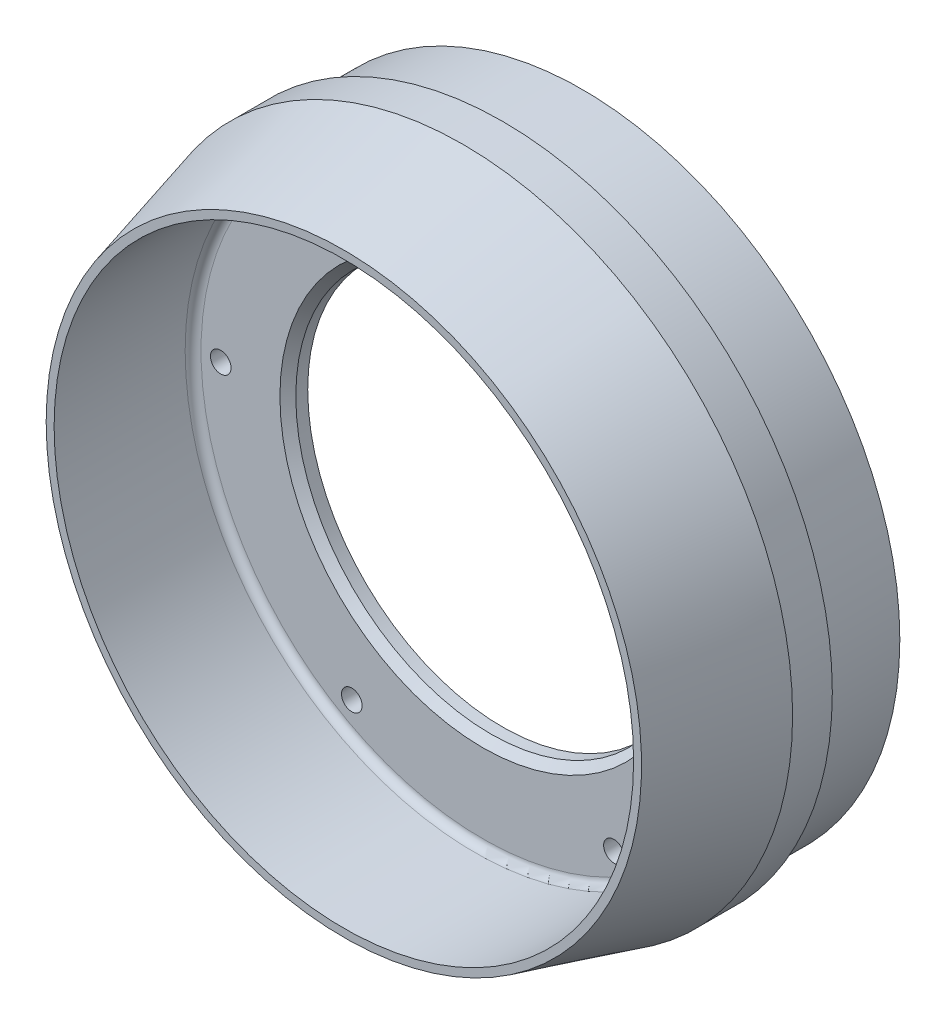
SolidWorks part; units mm, degrees
material "6061 Alloy"
ref_plane "Front Plane" through (0, 0, 0) normal (0, 0, 1) x (1, 0, 0)
ref_plane "Top Plane" through (0, 0, 0) normal (0, 1, 0) x (1, 0, 0)
ref_plane "Right Plane" through (0, 0, 0) normal (1, 0, 0) x (0, 0, -1)
sketch "Sketch2" plane through (0, 0, 0) normal (1, 0, 0) x (0, 0, -1)
  line L0 (-5, 83) -> (-35, 74.9615)
  line L1 (-35, 74.9615) -> (-35, 72.9615)
  line L2 (-35, 72.9615) -> (0, 72.9615)
  line L3 (0, 72.9615) -> (0, 49.1)
  line L5 (-5, 83) -> (5, 83)
  line L6 (0, 0) -> (0, 120.0745) construction
  line L8 (5, 77.5) -> (25, 77.5)
  line L9 (25, 77.5) -> (25, 80)
  line L10 (5, 80) -> (5, 83)
  line L11 (25, 80) -> (5, 80)
  line L12 (0, 49.1) -> (5, 49.1)
  line L14 (5, 49.1) -> (5, 77.5)
  point P1 (0, 0)
  point P7 (0, 0)
  point P9 (0, 0)
  point P16 (0, 83)
  dimension "D1" = 5
  dimension "D2" = 2.5
  dimension "D3" = 10
  dimension "D4" = 3
  dimension "D5" = 49.1
  dimension "D6" = 35
  dimension "D7" = 2
  dimension "D8" = 15
  dimension "D9" = 80
  dimension "D10" = 20
ref_axis "Axis1" through (0, 0, -77) along (0, 0, 1)
revolve "Revolve1" add sketch "Sketch2" angle 360 about axis through (0, 0, -77) along (0, 0, 1)
chamfer "Chamfer1" distance 2 angle 45 1 edges at (-77.5, 0, -25)
chamfer "Chamfer2" distance 2 angle 45 1 edges at (-49.1, 0, 0)
hole_wizard "#6 (0.204) Diameter Hole1" positions "Sketch4" profile "Sketch5" hole size "#6" standard "ANSI Inch"
sketch "Sketch4" plane through (0, 0, 0) normal (0, 0, 1) x (1, 0, 0)
  line L0 (0, 0) -> (0, 39.3331) construction
  line L2 (0, 0) -> (-33, 57.1577) construction
  circle A0 centre (0, 0) radius 66
  point P5 (-33, 57.1577)
  dimension "D2" = 132
  dimension "D1" = 30
sketch "Sketch5" plane through (-33, 57.1577, 0) normal (1, 0, 0) x (0, -1, 0)
  line L0 (0, 0) -> (0, 6.5557)
  line L1 (0, 6.5557) -> (2.5908, 4.999)
  line L2 (2.5908, 4.999) -> (2.5908, 0)
  line L5 (2.5908, 0) -> (0, 0)
  line L10 (0, 6.5557) -> (-2.5908, 4.999) construction
  line L11 (0, -6.35) -> (0, 107.95) construction
  dimension "Hole Dia." = 5.1816
  dimension "Hole Depth" = 4.999
  dimension "Drill Angle" = 118
pattern_circular "CirPattern1" count 6 over 360 about axis through (0, 0, 0) along (0, 0, 1) of "#6 (0.204) Diameter Hole1"
fillet "Fillet2" radius 5 1 edges at (-77.5, 0, -5)
fillet "Fillet3" radius 2 1 edges at (-72.9615, 0, 0)
